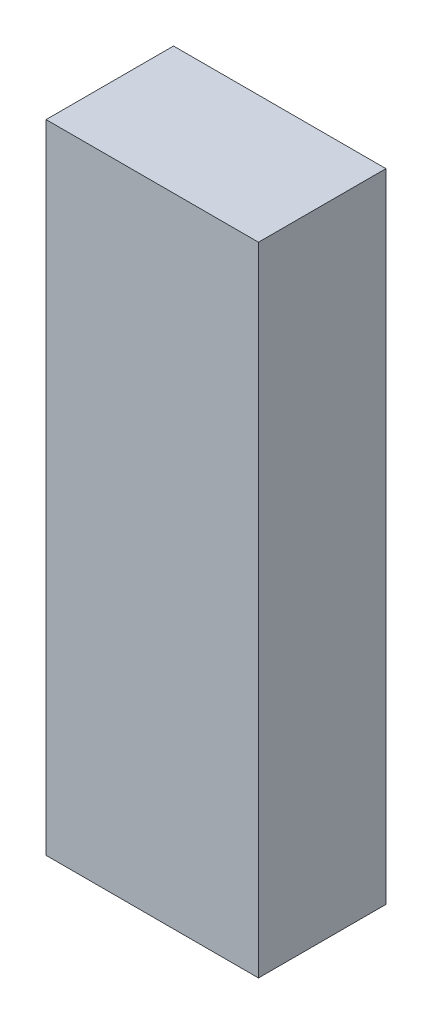
SolidWorks part; units mm, degrees
ref_plane "Alzado" through (0, 0, 0) normal (0, 0, 1) x (1, 0, 0)
ref_plane "Planta" through (0, 0, 0) normal (0, 1, 0) x (1, 0, 0)
ref_plane "Vista lateral" through (0, 0, 0) normal (1, 0, 0) x (0, 0, -1)
sketch "Croquis1" plane through (0, 0, 0) normal (0, 0, 1) x (1, 0, 0)
  line L1 (-25, -75) -> (25, -75)
  line L2 (-25, -75) -> (-25, 75)
  line L3 (-25, 75) -> (25, 75)
  line L4 (25, -75) -> (25, 75)
  line L5 (-25, -75) -> (25, 75) construction
  line L6 (-25, 75) -> (25, -75) construction
  point P0 (0, 0)
  dimension "D1" = 50
  dimension "D2" = 150
extrude "Saliente-Extruir1" add sketch "Croquis1" along normal blind 30
